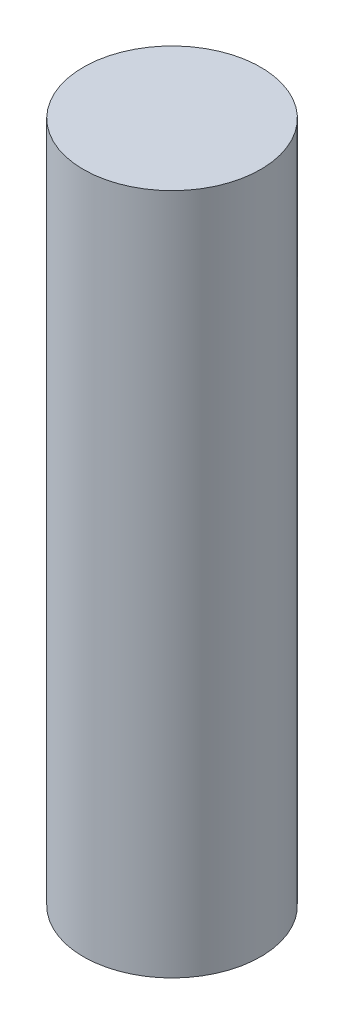
SolidWorks part; units mm, degrees
ref_plane "Front" through (0, 0, 0) normal (0, 0, 1) x (1, 0, 0)
ref_plane "Top" through (0, 0, 0) normal (0, 1, 0) x (1, 0, 0)
ref_plane "Right" through (0, 0, 0) normal (1, 0, 0) x (0, 0, -1)
sketch "Sketch1" plane through (0, 0, 0) normal (0, 1, 0) x (1, 0, 0)
  circle A0 centre (0, 0) radius 2.6
  dimension "D1" = 5.2
extrude "Boss-Extrude1" add sketch "Sketch1" along normal blind 20
